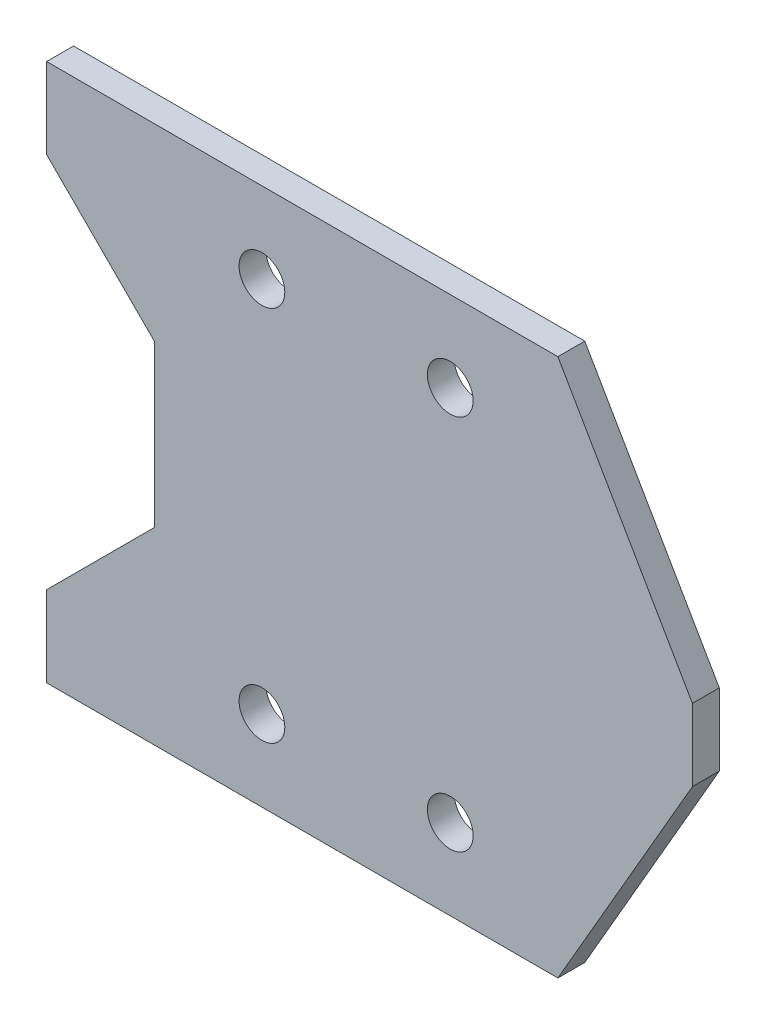
SolidWorks part; units mm, degrees
ref_plane "Ebene vorne" through (0, 0, 0) normal (0, 0, 1) x (1, 0, 0)
ref_plane "Ebene oben" through (0, 0, 0) normal (0, 1, 0) x (1, 0, 0)
ref_plane "Ebene rechts" through (0, 0, 0) normal (1, 0, 0) x (0, 0, -1)
sketch "Skizze1" plane through (0, 0, 0) normal (0, 0, 1) x (1, 0, 0)
  line L0 (0, 0) -> (146.5885, 0) construction
  line L1 (0, 15) -> (0, -15)
  line L2 (0, -15) -> (-20, -35)
  line L3 (-20, -35) -> (-20, -50)
  line L4 (-20, -50) -> (75, -50)
  line L5 (75, -50) -> (100, -6.6987)
  line L6 (100, -6.6987) -> (100, 6.6987)
  line L7 (75, 50) -> (100, 6.6987)
  line L8 (-20, 50) -> (75, 50)
  line L9 (-20, 35) -> (-20, 50)
  line L10 (0, 15) -> (-20, 35)
  circle A0 centre (20, 35) radius 4.25
  circle A1 centre (55, 35) radius 4.25
  circle A2 centre (20, -35) radius 4.25
  circle A3 centre (55, -35) radius 4.25
  point P10 (100, 0)
  point P22 (0, 0)
  point P24 (29.5128, 0)
  dimension "D7" = 8.5
  dimension "D8" = 8.5
  dimension "D9" = 8.5
  dimension "D10" = 8.5
  dimension "D1" = 100
  dimension "D2" = 30
  dimension "D3" = 120
  dimension "D4" = 90
  dimension "D5" = 25
  dimension "D6" = 120
  dimension "D11" = 35
  dimension "D12" = 35
  dimension "D13" = 35
  dimension "D14" = 35
  dimension "D15" = 40
  dimension "D16" = 35
  dimension "D17" = 35
  dimension "D18" = 20
  dimension "D19" = 40
extrude "Aufsatz-Linear austragen1" add sketch "Skizze1" along normal blind 5
